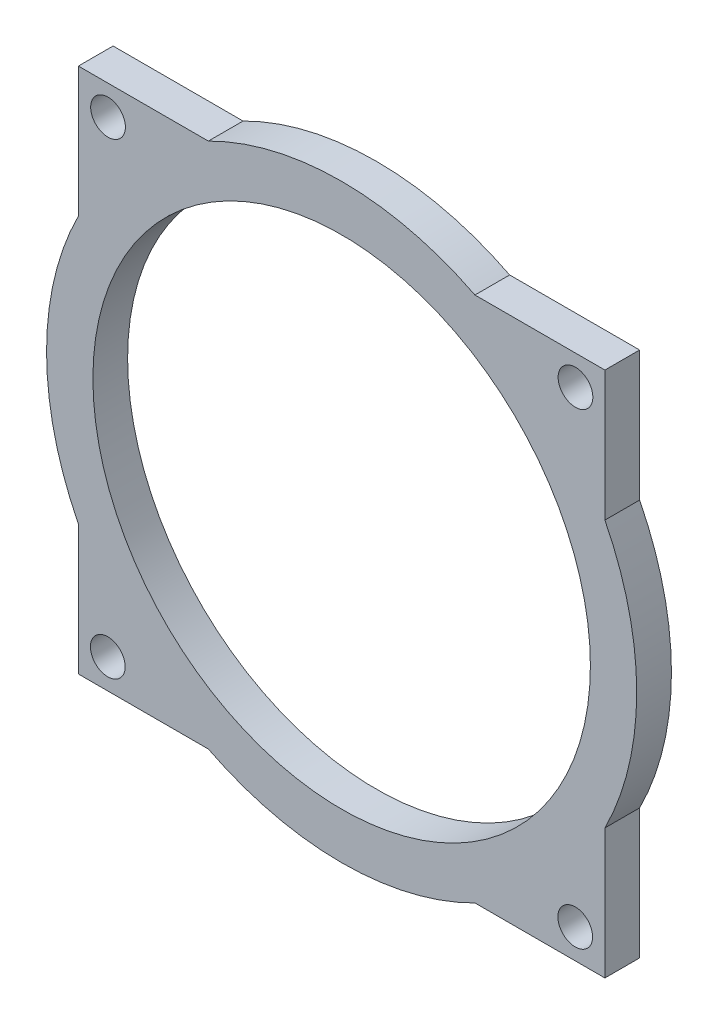
SolidWorks part; units mm, degrees
ref_plane "Front Plane" through (0, 0, 0) normal (0, 0, 1) x (1, 0, 0)
ref_plane "Top Plane" through (0, 0, 0) normal (0, 1, 0) x (1, 0, 0)
ref_plane "Right Plane" through (0, 0, 0) normal (1, 0, 0) x (0, 0, -1)
sketch "Sketch1" plane through (0, 0, 0) normal (0, 0, 1) x (1, 0, 0)
  line L0 (22.75, -22.75) -> (22.75, -11.519)
  line L1 (22.75, -12.5872) -> (22.75, 12.5872) construction
  line L2 (22.75, -22.75) -> (11.519, -22.75)
  line L3 (-22.75, -22.75) -> (-11.519, -22.75)
  line L4 (-12.5872, -22.75) -> (12.5872, -22.75) construction
  line L5 (-22.75, -22.75) -> (-22.75, -11.519)
  line L6 (-22.75, 12.5872) -> (-22.75, -12.5872) construction
  line L7 (-22.75, 22.75) -> (-22.75, 11.519)
  line L8 (-22.75, 22.75) -> (-11.519, 22.75)
  line L9 (22.75, 22.75) -> (11.519, 22.75)
  line L10 (22.75, 22.75) -> (22.75, 11.519)
  arc A0 (-22.75, 11.519) -> (11.519, -22.75) centre (0, 0) ccw
  arc A1 (11.519, 22.75) -> (-11.519, 22.75) centre (0, 0) ccw
  circle A2 centre (20.1888, -20.2074) radius 1.5
  circle A3 centre (-20.2074, -20.1888) radius 1.5
  circle A8 centre (0, 0) radius 21.4962
  circle A9 centre (0, 0) radius 25.5 construction
  arc A10 (22.75, -11.519) -> (22.75, 11.519) centre (0, 0) ccw
  circle A11 centre (-20.1888, 20.2074) radius 1.5
  circle A12 centre (20.2074, 20.1888) radius 1.5
  point P11 (0, 0)
  dimension "D1" = 3
  dimension "D2" = 4
extrude "Boss-Extrude1" add sketch "Sketch1" along normal blind 3 contours L0 A10 L10 L9 A1 L8 L7 A0 L2 A12 A11 A2 A8 | A0 L5 L3 A3
